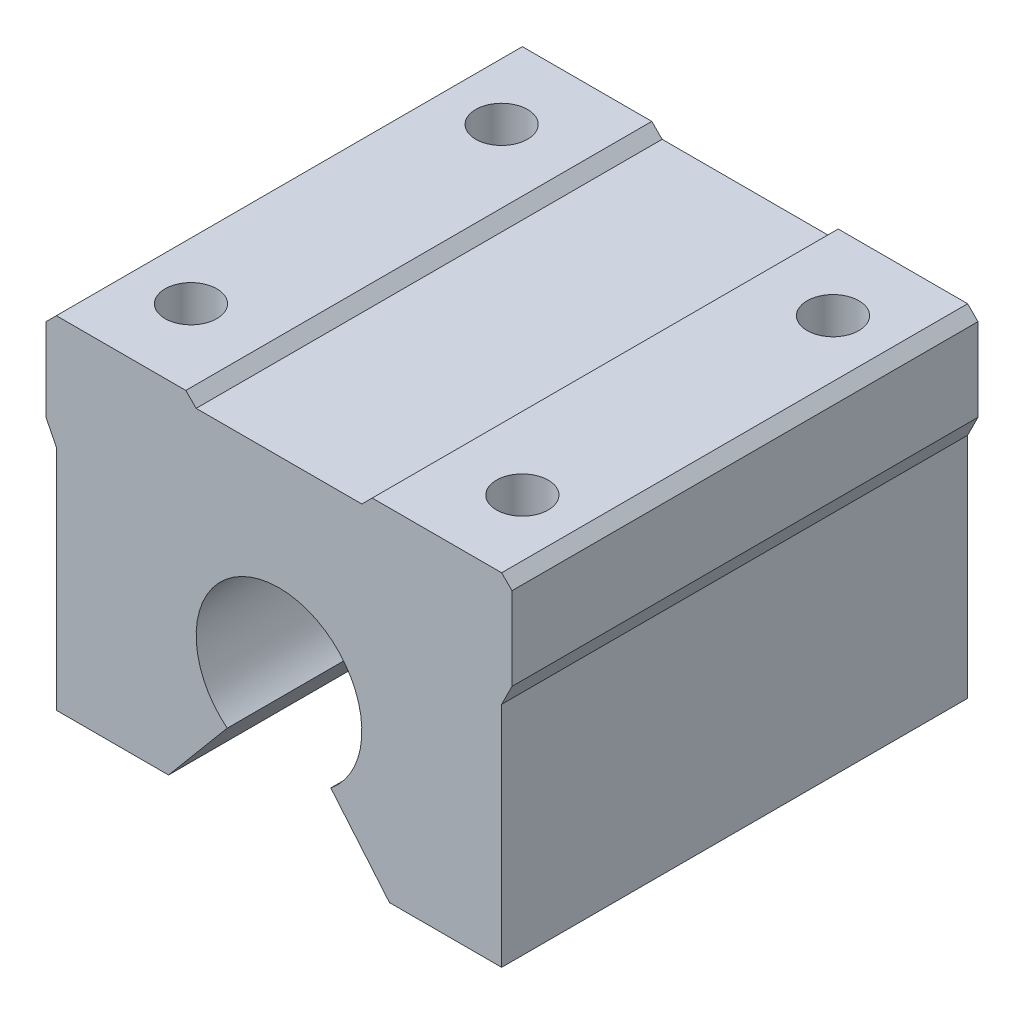
SolidWorks part; units mm, degrees
material "1.0037 (S235JR)"
ref_plane "Płaszczyzna przednia" through (0, 0, 0) normal (0, 0, 1) x (1, 0, 0)
ref_plane "Płaszczyzna górna" through (0, 0, 0) normal (0, 1, 0) x (1, 0, 0)
ref_plane "Płaszczyzna prawa" through (0, 0, 0) normal (1, 0, 0) x (0, 0, -1)
sketch "Szkic1" plane through (0, 0, 0) normal (0, 0, 1) x (1, 0, 0)
  line L0 (0, 0) -> (0, 37.0346) construction
  line L1 (8, 32) -> (-8, 32)
  line L2 (-10.6681, 0) -> (-5, 6.755)
  line L3 (-9, 33) -> (-21.5, 33)
  line L4 (-22.5, 32) -> (-22.5, 24)
  line L5 (-22.5, 24) -> (-21.5, 22)
  line L6 (-21.5, 22) -> (-21.5, 0)
  line L7 (-21.5, 0) -> (-10.6681, 0)
  line L8 (-21.5, 33) -> (-22.5, 32)
  line L9 (-8, 32) -> (-9, 33)
  line L10 (8, 32) -> (9, 33)
  line L11 (21.5, 33) -> (22.5, 32)
  line L12 (21.5, 0) -> (10.6681, 0)
  line L13 (21.5, 22) -> (21.5, 0)
  line L14 (22.5, 24) -> (21.5, 22)
  line L15 (22.5, 32) -> (22.5, 24)
  line L16 (9, 33) -> (21.5, 33)
  line L17 (10.6681, 0) -> (5, 6.755)
  arc A0 (5, 6.755) -> (-5, 6.755) centre (0, 13) ccw
  point P7 (-22.5, 33)
  point P13 (0, 32)
  point P24 (22.5, 33)
  dimension "R" = 8
  dimension "E" = 22.5
  dimension "F" = 33
  dimension "h" = 20
  dimension "T" = 9
  dimension "D10" = 32
  dimension "D6" = 1
  dimension "D8" = 2
  dimension "h1" = 10
  dimension "O" = 80
  dimension "D3" = 1
  dimension "D2" = 12.5
extrude "Dodanie-wyciągnięcie1" add sketch "Szkic1" along normal blind 45
sketch "Szkic2" plane through (0, 33, 0) normal (0, 1, 0) x (1, 0, 0)
  line L0 (0, 0) -> (0, -45) construction
  line L1 (8, -45) -> (-8, -45) construction
  line L2 (-22.5, -22.5) -> (22.5, -22.5) construction
  line L5 (-22.5, -45) -> (-22.5, 0) construction
  line L6 (22.5, -45) -> (22.5, 0) construction
  circle A0 centre (-16, -37.5) radius 2.5
  circle A1 centre (-16, -7.5) radius 2.5
  circle A2 centre (16, -7.5) radius 2.5
  circle A3 centre (16, -37.5) radius 2.5
  dimension "S" = 5
  dimension "B" = 32
  dimension "D1" = 16
  dimension "C" = 30
  dimension "D2" = 15
extrude "Wytnij-wyciągnięcie1" cut sketch "Szkic2" against normal blind 12
sketch "Szkic3" plane through (0, 21, 0) normal (0, 1, 0) x (1, 0, 0)
  circle A0 centre (16, -7.5) radius 2.5 construction
  circle A1 centre (-16, -7.5) radius 2.5 construction
  circle A2 centre (-16, -37.5) radius 2.5 construction
  circle A3 centre (16, -37.5) radius 2.5 construction
  circle A4 centre (16, -7.5) radius 2.5
  circle A5 centre (-16, -7.5) radius 2.5
  circle A6 centre (-16, -37.5) radius 2.5
  circle A7 centre (16, -37.5) radius 2.5
extrude "Wytnij-wyciągnięcie2" cut sketch "Szkic3" against normal blind 12 draft 58
equation "\"D1@Szkic2\" = \"B@Szkic2\"/2"
equation "\"D2@Szkic2\" = \"C@Szkic2\"/2"
equation "\"D10@Szkic1\" = \"F@Szkic1\"-1"
equation "\"D2@Szkic1\"=(\"D1@Szkic2\"-(\"S@Szkic2\"/2+1))"
